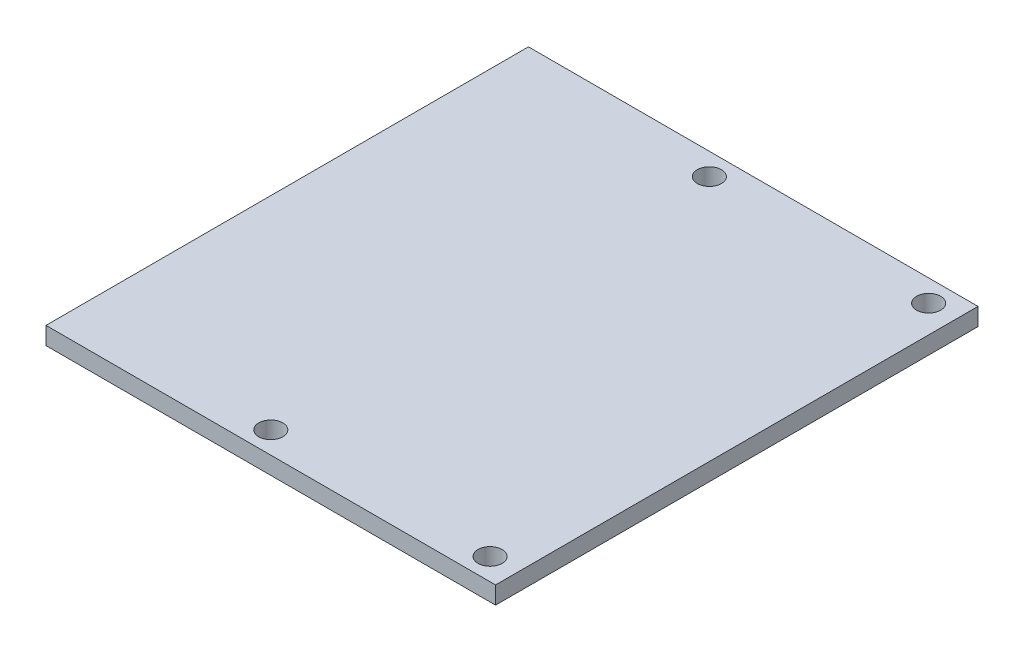
SolidWorks part; units mm, degrees
ref_plane "Front Plane" through (0, 0, 0) normal (0, 0, 1) x (1, 0, 0)
ref_plane "Top Plane" through (0, 0, 0) normal (0, 1, 0) x (1, 0, 0)
ref_plane "Right Plane" through (0, 0, 0) normal (1, 0, 0) x (0, 0, -1)
sketch "Sketch1" plane through (0, 0, 0) normal (0, 1, 0) x (1, 0, 0)
  line L1 (0, 0) -> (41, 0)
  line L2 (0, 0) -> (0, 44)
  line L3 (0, 44) -> (41, 44)
  line L4 (41, 0) -> (41, 44)
  circle A0 centre (38.5, 2) radius 1.1
  circle A1 centre (18.5, 2) radius 1.1
  circle A2 centre (38.5, 42) radius 1.1
  circle A3 centre (18.5, 42) radius 1.1
  point P13 (25.5, 21)
  point P14 (36.5, 12)
  point P15 (9.5, 30)
  point P16 (4.8688, 11.6361)
  dimension "D3" = 2.2
  dimension "D4" = 18.5
  dimension "D1" = 44
  dimension "D2" = 41
  dimension "D5" = 2
  dimension "D6" = 2
  dimension "D7" = 38.5
  dimension "D8" = 25.5
  dimension "D9" = 23
  dimension "D10" = 36.5
  dimension "D11" = 32
  dimension "D12" = 9.5
  dimension "D13" = 14
extrude "Boss-Extrude1" add sketch "Sketch1" along normal blind 1.6
